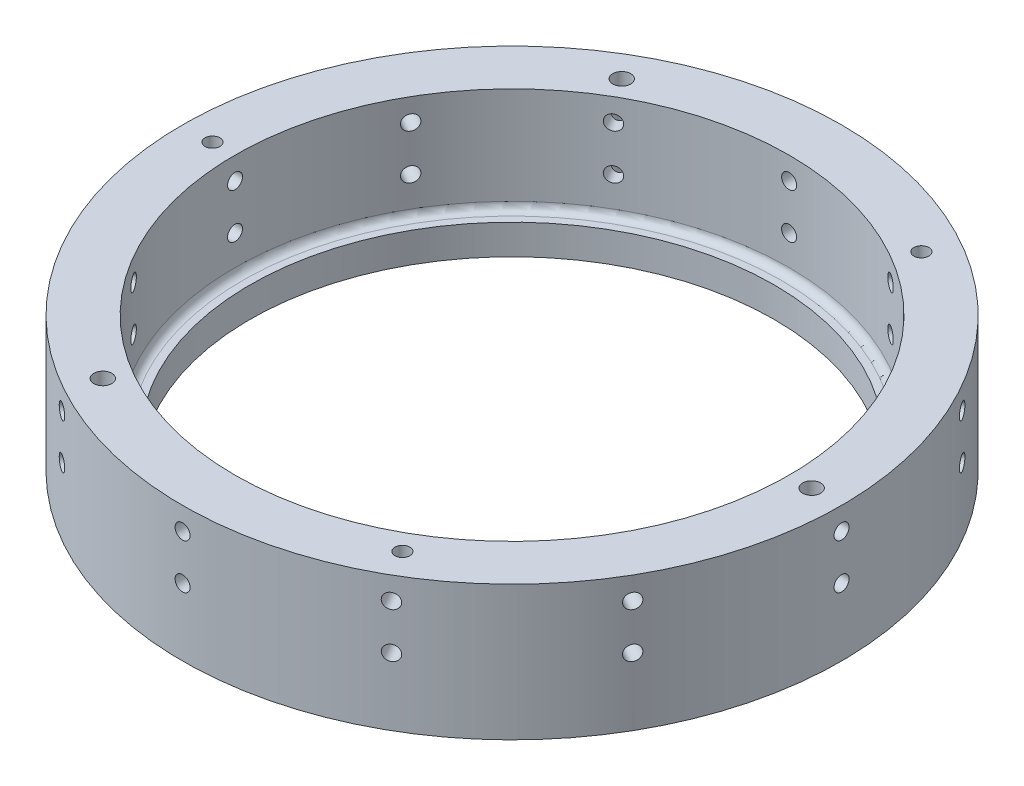
SolidWorks part; units mm, degrees
material "延性铁"
ref_plane "前视基准面" through (0, 0, 0) normal (0, 0, 1) x (1, 0, 0)
ref_plane "上视基准面" through (0, 0, 0) normal (0, 1, 0) x (1, 0, 0)
ref_plane "右视基准面" through (0, 0, 0) normal (1, 0, 0) x (0, 0, -1)
sketch "草图1" plane through (0, 0, 0) normal (1, 0, 0) x (0, 0, -1)
  line L0 (0, 0) -> (0, 159.2157) construction
  line L1 (-110, 45) -> (-110, 0)
  line L2 (-110, 0) -> (-87.5, 0)
  line L3 (-87.5, 0) -> (-87.5, 10)
  line L4 (-87.5, 10) -> (-92.5, 10)
  line L5 (-92.5, 10) -> (-92.5, 45)
  line L6 (-92.5, 45) -> (-110, 45)
  dimension "D1" = 175
  dimension "D2" = 185
  dimension "D3" = 45
  dimension "D4" = 10
  dimension "D5" = 220
revolve "旋转1" add sketch "草图1" angle 360 about L0
sketch "草图2" plane through (0, 45, 0) normal (0, 1, 0) x (1, 0, 0)
  circle A0 centre (100, 0) radius 3
  dimension "D2" = 6
  dimension "D4" = 100
extrude "切除-拉伸1" cut sketch "草图2" against normal through all
hole_wizard "M6 螺纹孔1" positions "草图3" profile "草图4" tap size "M6" standard "GB"
sketch "草图3" plane through (0, 45, 0) normal (0, 1, 0) x (1, 0, 0)
  line L0 (-100, 0) -> (0, 0) construction
  line L1 (0, 0) -> (100, 0) construction
  point P0 (-100, 0)
sketch "草图4" plane through (-100, 45, 0) normal (1, 0, 0) x (0, 0, 1)
  line L0 (0, 0) -> (0, 16.5022)
  line L1 (0, 16.5022) -> (2.5, 15)
  line L2 (2.5, 15) -> (2.5, 0)
  line L5 (2.5, 0) -> (0, 0)
  line L10 (0, 16.5022) -> (-2.5, 15) construction
  line L11 (0, -6.35) -> (0, 107.95) construction
  dimension "螺纹孔钻头直径" = 5
  dimension "螺纹孔钻头深度" = 15
  dimension "导头角度" = 118
cosmetic thread "孔螺蚊线2" parameters "D1"=12, "D2"=6
hole_wizard "M6 螺纹孔3" positions "草图7" profile "草图8" tap size "M6" standard "GB"
sketch "草图7" plane through (0, 0, 0) normal (0, 0, 1) x (1, 0, 0)
  line L0 (92.5, 45) -> (-92.5, 45) construction
  line L1 (110, 45) -> (-110, 45) construction
  point P0 (0, 37.5)
  point P7 (0, 22.5)
  dimension "D1" = 7.5
  dimension "D2" = 22.5
sketch "草图8" plane through (0, 37.5, 0) normal (1, 0, 0) x (0, 1, 0)
  line L0 (0, 0) -> (0, 110)
  line L1 (0, 110) -> (2.5, 110)
  line L2 (2.5, 110) -> (2.5, 0)
  line L5 (2.5, 0) -> (0, 0)
  line L11 (0, -6.35) -> (0, 107.95) construction
  dimension "通孔螺纹孔钻头直径" = 5
  dimension "通孔螺纹孔钻头深度" = 110
cosmetic thread "孔螺蚊线4" parameters "D2"=6
cosmetic thread "孔螺蚊线5" parameters "D2"=6
sketch "草图9" plane through (0, 45, 0) normal (0, 1, 0) x (1, 0, 0)
  circle A0 centre (-100, 0) radius 2.5
  dimension "D1" = 5
extrude "切除-拉伸2" cut sketch "草图9" against normal through all
pattern_circular "阵列(圆周)1" count 3 over 360 about axis through (0, 0, 0) along (0, 1, 0) of "切除-拉伸1", "M6 螺纹孔1", "切除-拉伸2"
fillet "圆角1" radius 2.5 1 edges at (0, 10, -92.5)
pattern_circular "阵列(圆周)2" count 12 over 360 about axis through (0, 0, 0) along (0, -1, 0) of "M6 螺纹孔3"
